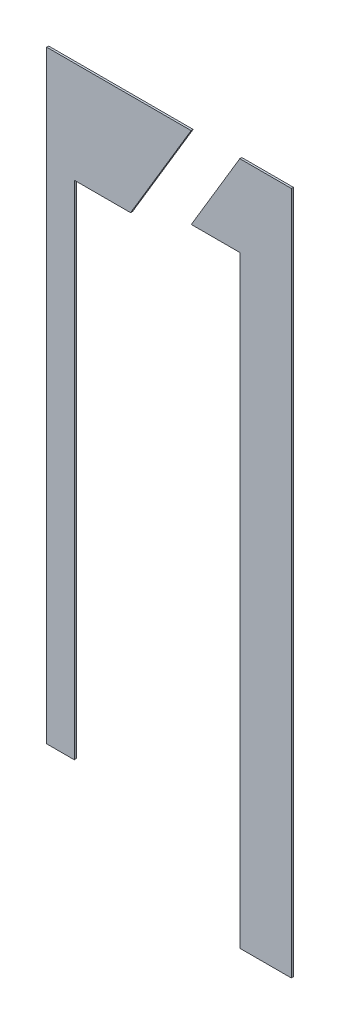
SolidWorks part; units mm, degrees
ref_plane "Front Plane" through (0, 0, 0) normal (0, 0, 1) x (1, 0, 0)
ref_plane "Top Plane" through (0, 0, 0) normal (0, 1, 0) x (1, 0, 0)
ref_plane "Right Plane" through (0, 0, 0) normal (1, 0, 0) x (0, 0, -1)
sketch "Sketch3" plane through (0, 0, 0) normal (0, 0, 1) x (1, 0, 0)
  line L0 (12.1338, 28.6656) -> (24.1989, 48.8652)
  line L1 (24.1989, 48.8652) -> (37.002, 48.8652)
  line L2 (37.002, 48.8652) -> (37.002, -121.1348)
  line L3 (37.002, -121.1348) -> (24.1989, -121.1348)
  line L4 (24.1989, -121.1348) -> (24.1989, 28.6656)
  line L5 (24.1989, 28.6656) -> (12.1338, 28.6656)
  line L6 (-2.9569, 23.6557) -> (12.1005, 48.8652)
  line L7 (12.1005, 48.8652) -> (-23.8149, 48.8652)
  line L8 (-23.8149, 48.8652) -> (-23.8149, -101.1348)
  line L9 (-23.8149, -101.1348) -> (-16.9569, -101.1348)
  line L10 (-16.9569, -101.1348) -> (-16.9569, 23.6557)
  line L11 (-16.9569, 23.6557) -> (-2.9569, 23.6557)
  line L12 (-2.9286, 71.0642) -> (0, -122.4006) construction
  point P14 (0, 0)
  point P15 (0, 0)
  point P16 (0, 0)
  point P17 (0, 0)
  dimension "D1" = 170
  dimension "D2" = 6.858
  dimension "D3" = 150
  dimension "D4" = 14
  dimension "D5" = 29.0908
  dimension "D6" = 0
  dimension "D7" = 12.0984
  dimension "D8" = 29.364
extrude "Boss-Extrude2" add sketch "Sketch3" along normal blind 0.5
